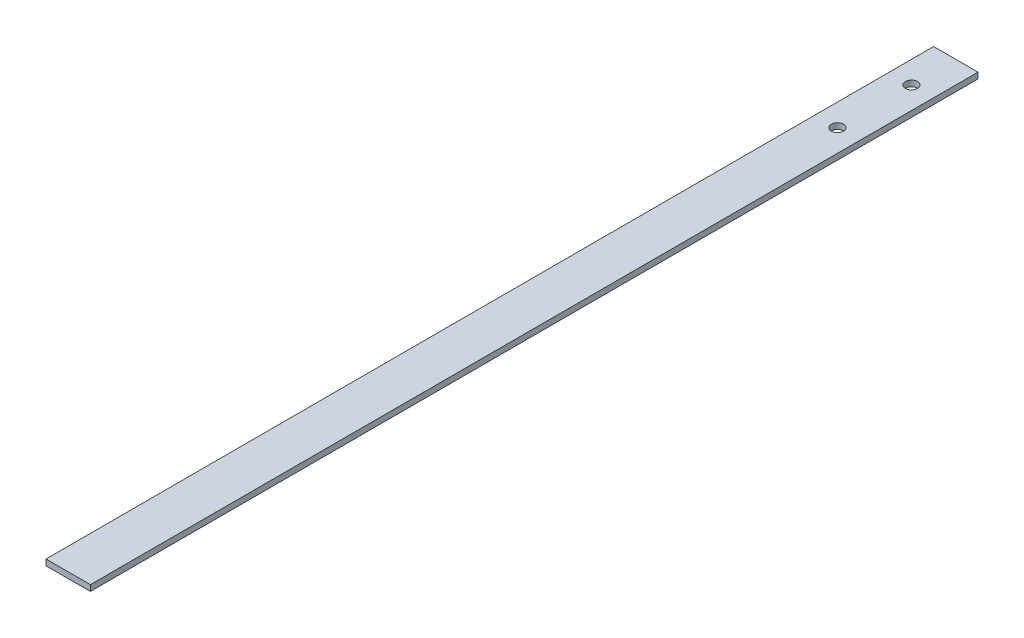
SolidWorks part; units mm, degrees
material "1060 Alloy"
ref_plane "Front" through (0, 0, 0) normal (0, 0, 1) x (1, 0, 0)
ref_plane "Top" through (0, 0, 0) normal (0, 1, 0) x (1, 0, 0)
ref_plane "Right" through (0, 0, 0) normal (1, 0, 0) x (0, 0, -1)
sketch "Sketch1" plane through (0, 0, 0) normal (0, 0, 1) x (1, 0, 0)
  line L1 (0, 0) -> (15, 0)
  line L2 (0, 0) -> (0, 2)
  line L3 (0, 2) -> (15, 2)
  line L4 (15, 0) -> (15, 2)
  dimension "D1" = 15
  dimension "D2" = 2
extrude "Boss-Extrude1" add sketch "Sketch1" along normal blind 300
sketch "Sketch2" plane through (0, 2, 0) normal (0, 1, 0) x (1, 0, 0)
  line L0 (15, 0) -> (0, 0) construction
  circle A0 centre (7.5, -15) radius 2.05
  circle A1 centre (7.5, -40) radius 2.05
  point P7 (7.5, 0)
  dimension "D1" = 4.1
  dimension "D2" = 4.1
  dimension "D3" = 15
  dimension "D4" = 25
extrude "Cut-Extrude1" cut sketch "Sketch2" against normal through all
